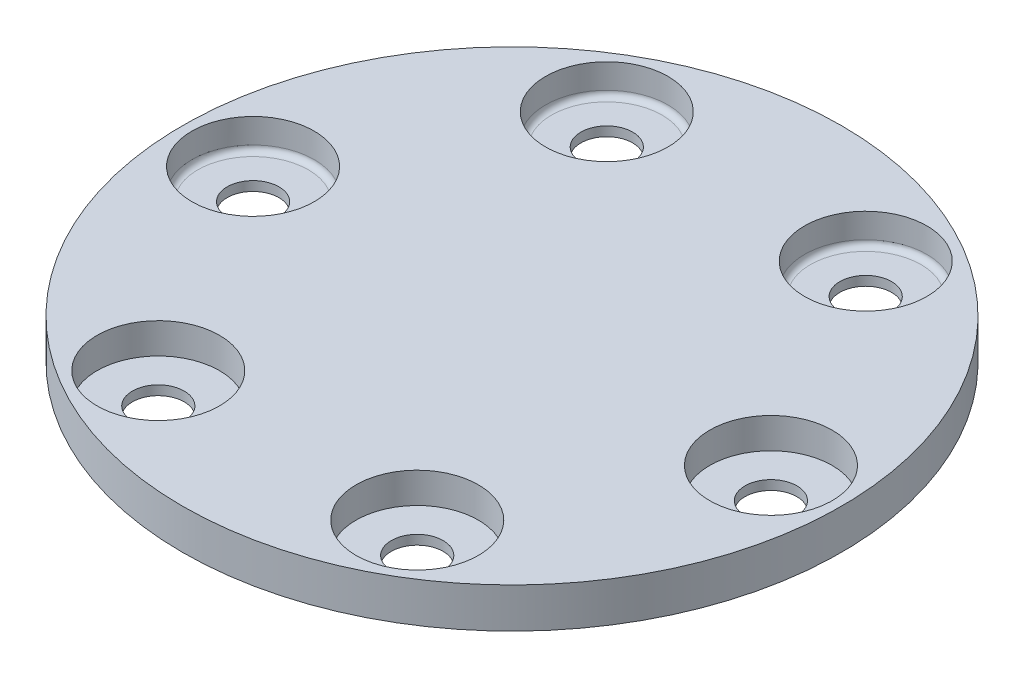
SolidWorks part; units mm, degrees
material "1060 Alloy"
ref_plane "Front Plane" through (0, 0, 0) normal (0, 0, 1) x (1, 0, 0)
ref_plane "Top Plane" through (0, 0, 0) normal (0, 1, 0) x (1, 0, 0)
ref_plane "Right Plane" through (0, 0, 0) normal (1, 0, 0) x (0, 0, -1)
sketch "Sketch1" plane through (0, 0, 0) normal (0, 1, 0) x (1, 0, 0)
  circle A0 centre (0, 0) radius 14
  dimension "D1" = 28
extrude "Boss-Extrude1" add sketch "Sketch1" along normal blind 1.7
sketch "Sketch7" plane through (0, 1.7, 0) normal (0, 1, 0) x (1, 0, 0)
  circle A0 centre (0, -10.25) radius 0.25
  circle A1 centre (0, 0) radius 9.8
  dimension "D1" = 0.5
  dimension "D2" = 10.25
  dimension "D3" = 19.6
sketch "Sketch8" plane through (0, 1.7, 0) normal (0, 1, 0) x (1, 0, 0)
  line L0 (0, 0) -> (13.2071, 13.2071) construction
  circle A0 centre (7.7782, 7.7782) radius 1
  dimension "D1" = 2
  dimension "D2" = 11
sketch "Sketch9" plane through (0, 1.7, 0) normal (0, 1, 0) x (1, 0, 0)
  circle A0 centre (0, 0) radius 11
  dimension "D1" = 22
hole_wizard "CBORE for M5 Hex Head Bolt1" positions "Sketch13" profile "Sketch14" counterbore size "M5" standard "ISO"
sketch "Sketch13" plane through (0, 1.7, 0) normal (0, 1, 0) x (1, 0, 0)
  circle A0 centre (0, 0) radius 11 construction
  point P0 (-11, 0)
  dimension "D1" = 11
sketch "Sketch14" plane through (-11, 1.7, 0) normal (1, 0, 0) x (0, 0, 1)
  line L0 (0, 0) -> (0, 5.6609)
  line L1 (0, 5.6609) -> (1.1, 5)
  line L2 (1.1, 5) -> (1.1, 1.3)
  line L3 (1.1, 1.3) -> (2.6, 1.3)
  line L4 (2.6, 1.3) -> (2.6, 0)
  line L5 (2.6, 0) -> (0, 0)
  line L10 (0, 5.6609) -> (-1.1, 5) construction
  line L11 (0, -6.35) -> (0, 107.95) construction
  dimension "Hole Dia." = 2.2
  dimension "Hole Depth" = 5
  dimension "C'Bore Dia." = 5.2
  dimension "C'Bore Depth" = 1.3
  dimension "Drill Angle" = 118
pattern_circular "CirPattern1" count 6 over 360 about axis through (0, 0, 0) along (0, 1, 0) of "CBORE for M5 Hex Head Bolt1"
fillet "Fillet1" radius 0.25 3 edges at (-11, 0.4, 2.6) (3.2483, 0.4, -10.8263) (-7.7517, 0.4, -8.2263)
